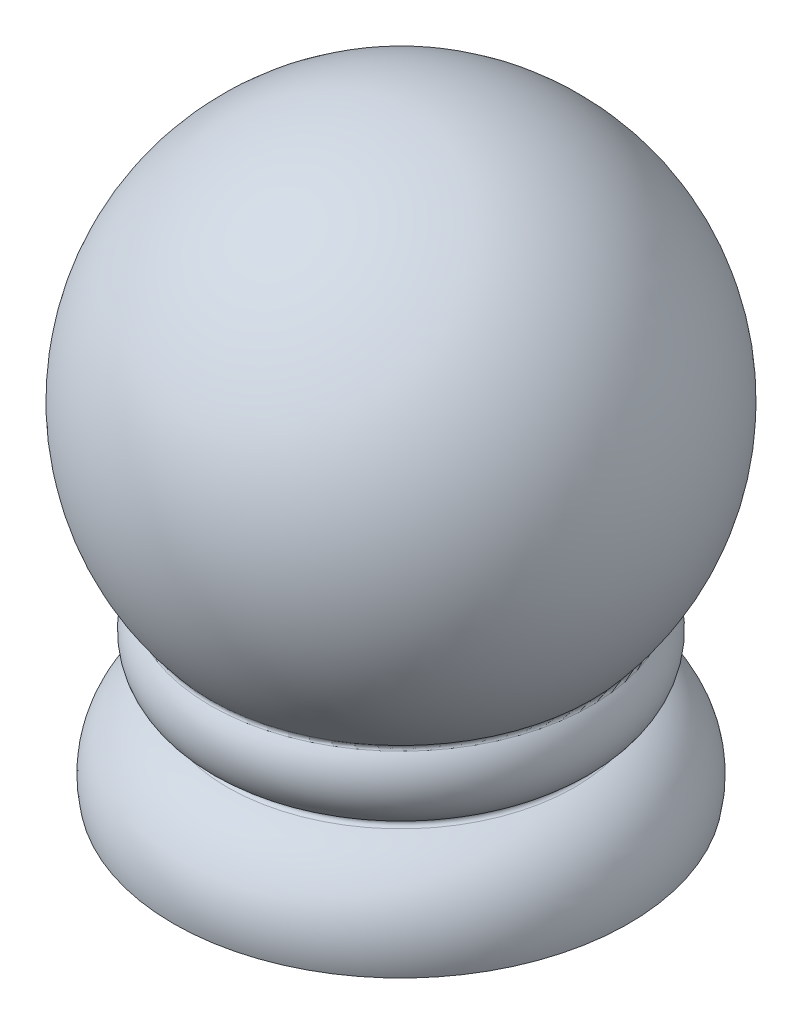
SolidWorks part; units mm, degrees
material "PW50:16:C1:0:1:2:Re:26:"
ref_plane "Plane1" through (0, 0, 0) normal (0, 0, 1) x (1, 0, 0)
ref_plane "Plane2" through (0, 0, 0) normal (0, 1, 0) x (1, 0, 0)
ref_plane "Plane3" through (0, 0, 0) normal (1, 0, 0) x (0, 0, -1)
other "Configuration Table"
sketch "Sketch1" plane through (0, 0, 0) normal (0, 0, 1) x (1, 0, 0)
  line L0 (0, 77.2442) -> (0, -46.8583) construction
  line L1 (0, 0) -> (14.5, 0)
  line L2 (0, 37.583) -> (0, 0)
  arc A0 (14.5, 0) -> (11.0578, 5.7997) centre (9.6042, 1.0157) ccw
  arc A1 (11.0259, 6.2661) -> (12.1322, 10.8428) centre (9.7717, 8.9913) ccw
  arc A2 (11.0259, 6.2661) -> (11.0578, 5.7997) centre (11.1305, 6.039) ccw
  arc A3 (0, 37.583) -> (12.1392, 11.16) centre (0, 21.583) cw
  arc A4 (12.1392, 11.16) -> (12.1322, 10.8428) centre (12.3289, 10.9971) ccw
  point P11 (10, 6)
  point P16 (12, 11)
  dimension "D4" = 5
  dimension "D7" = 3
  dimension "D8" = 0.25
  dimension "D9" = 16
  dimension "D10" = 0.25
  dimension "D1" = 14.5
  dimension "D2" = 10
  dimension "D3" = 6
  dimension "D5" = 12
  dimension "D6" = 5
revolve "Base-Revolve" add sketch "Sketch1" angle 360 about L0
sketch "Sketch4" plane through (0, 0, 0) normal (0, 0, 1) x (1, 0, 0)
  line L0 (13.5, -1.8614) -> (13.5, 2)
  line L1 (13.5, 2) -> (12.5, 2)
  line L2 (12.5, 2) -> (10, 6)
  line L3 (10, 6) -> (10, 30)
  line L4 (10, 30) -> (0, 30)
  line L5 (0, 77.2442) -> (0, -46.8583) construction
  line L6 (0, 30) -> (0, -1.8614)
  line L7 (0, 39.3418) -> (0, -12.3309) construction
  line L8 (0, -1.8614) -> (13.5, -1.8614)
  dimension "D1" = 2
  dimension "D2" = 13.5
  dimension "D3" = 1
  dimension "D4" = 10
  dimension "D5" = 6
  dimension "D6" = 30
revolve "Cut-Revolve1" cut sketch "Sketch4" angle 360 about L7
sketch "Sketch5" plane through (0, 30, 0) normal (0, -1, 0) x (1, 0, 0)
  circle A0 centre (0, 0) radius 4.5
  dimension "D1" = 9
extrude "Boss-Extrude1" add sketch "Sketch5" along normal blind 6 draft 1
sketch "Sketch6" plane through (0, 24, 0) normal (0, -1, 0) x (1, 0, 0)
  circle A0 centre (0, 0) radius 3.25
  dimension "D1" = 6.5
extrude "Cut-Extrude2" cut sketch "Sketch6" against normal blind 10
fillet "Fillet1" radius 0.25 2 edges at (0, 2, 12.5) (0, 24, -4.3953)
fillet "Fillet2" radius 2 1 edges at (0, 30, 10)
